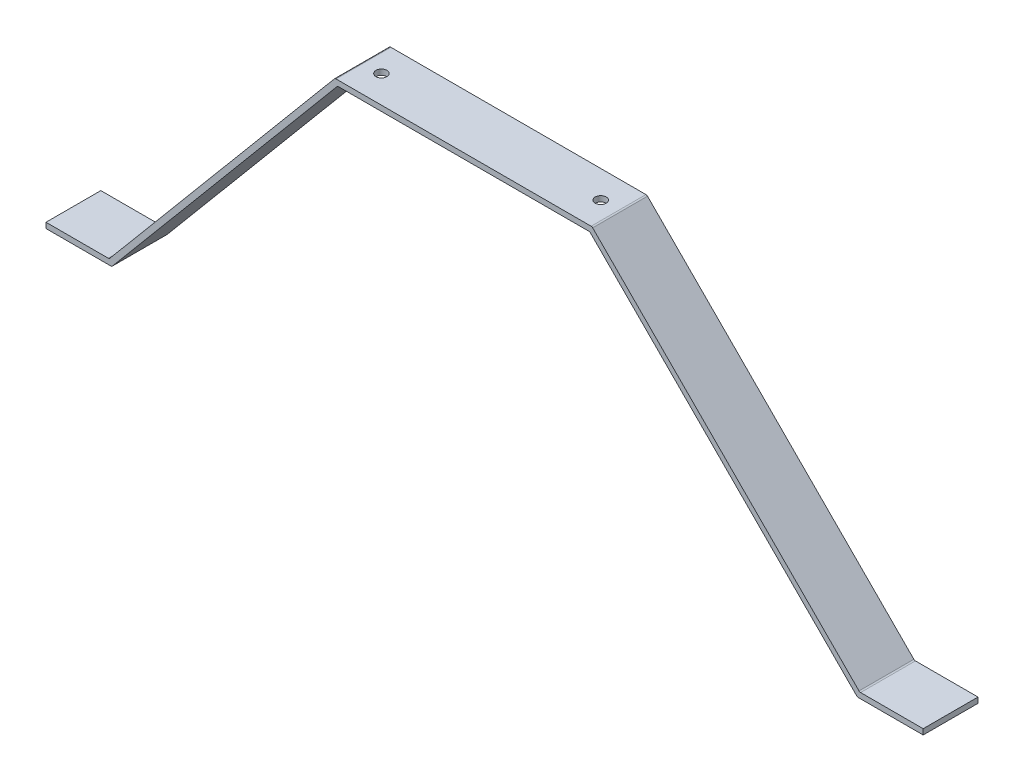
SolidWorks part; units mm, degrees
ref_plane "Płaszczyzna przednia" through (0, 0, 0) normal (0, 0, 1) x (1, 0, 0)
ref_plane "Płaszczyzna górna" through (0, 0, 0) normal (0, 1, 0) x (1, 0, 0)
ref_plane "Płaszczyzna prawa" through (0, 0, 0) normal (1, 0, 0) x (0, 0, -1)
sketch "Szkic1" plane through (0, 0, 0) normal (0, 0, 1) x (1, 0, 0)
  line L0 (0, 0) -> (60, 0)
  line L1 (0, 5) -> (57.6682, 5)
  line L2 (263.5882, 250.45) -> (57.6682, 5)
  line L3 (265.92, 245.45) -> (60, 0)
  line L4 (265.92, 245.45) -> (495.92, 245.45)
  line L5 (263.5882, 250.45) -> (497.9993, 250.45)
  line L6 (740, 0) -> (800, 0)
  line L7 (495.92, 245.45) -> (740, 0)
  line L8 (497.9993, 250.45) -> (742.0793, 5)
  line L9 (742.0793, 5) -> (800, 5)
  line L10 (0, 5) -> (0, 0)
  line L11 (800, 5) -> (800, 0)
  dimension "D1" = 60
  dimension "D2" = 5
  dimension "D4" = 230
  dimension "D5" = 680
  dimension "D6" = 60
extrude "Dodanie-wyciągnięcie1" add sketch "Szkic1" along normal blind 50
fillet "Zaokrąglenie1" radius 2 8 edges at (57.6682, 5, 25) (60, 0, 25) (265.92, 245.45, 25) (263.5882, 250.45, 25) (495.92, 245.45, 25) (740, 0, 25) (742.0793, 5, 25) (497.9993, 250.45, 25)
sketch "Szkic2" plane through (0, 250.45, 0) normal (0, 1, 0) x (1, 0, 0)
  circle A0 centre (480.9195, -25) radius 5
  circle A1 centre (280.9195, -25) radius 5
  dimension "D1" = 10
  dimension "D2" = 10
extrude "Wytnij-wyciągnięcie1" cut sketch "Szkic2" against normal up to next
